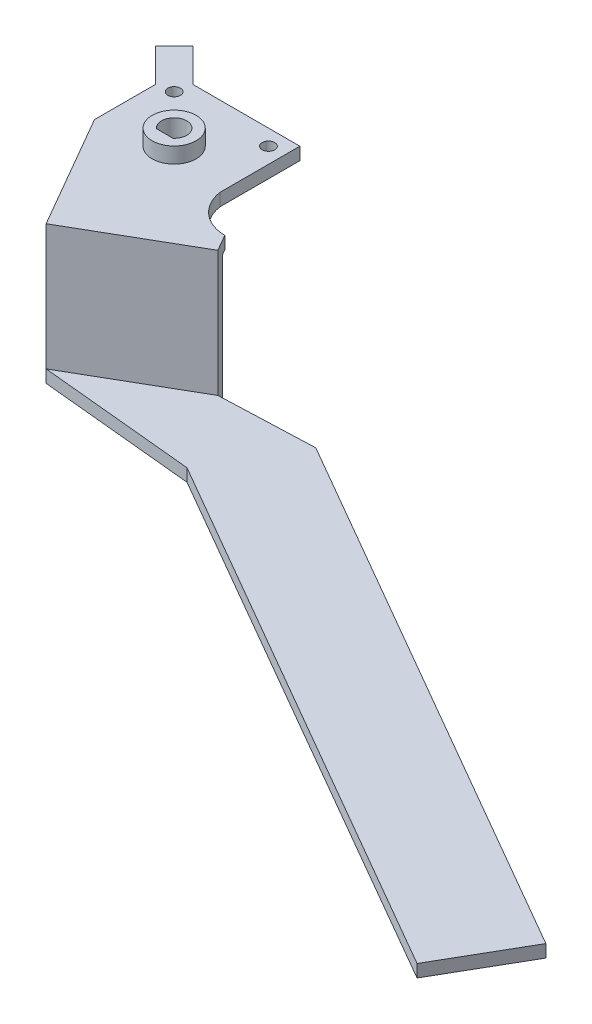
SolidWorks part; units mm, degrees
ref_plane "Front Plane" through (0, 0, 0) normal (0, 0, 1) x (1, 0, 0)
ref_plane "Top Plane" through (0, 0, 0) normal (0, 1, 0) x (1, 0, 0)
ref_plane "Right Plane" through (0, 0, 0) normal (1, 0, 0) x (0, 0, -1)
sketch "Sketch1" plane through (0, 0, 0) normal (0, 1, 0) x (1, 0, 0)
  line L0 (0, -4) -> (0, -3) construction
  line L1 (-20, 20) -> (20, 20) construction
  line L2 (-20, 20) -> (-20, -20) construction
  line L3 (-20, -20) -> (20, -20) construction
  line L4 (20, 20) -> (20, -20) construction
  line L5 (-20, 20) -> (20, -20) construction
  line L6 (-20, -20) -> (20, 20) construction
  line L11 (0, 0) -> (35.9445, -62.2576) construction
  line L12 (-20, -20) -> (20, -20) construction
  line L13 (-2.6458, -3) -> (2.6458, -3)
  line L14 (-20, -20) -> (-20, -22) construction
  line L15 (-20, -22) -> (20, -22) construction
  line L16 (20, -20) -> (20, -22) construction
  line L17 (1, -41.7321) -> (35.641, -21.7321)
  line L18 (35.641, -21.7321) -> (32.641, -16.5359)
  line L19 (1, -41.7321) -> (-20, -5.359)
  line L20 (-20, 20) -> (-20, -5.359) construction
  line L21 (20, 20) -> (20, -5.359)
  line L22 (-14, 20) -> (-24.6066, 30.6066)
  line L23 (-24.6066, 30.6066) -> (-30.6066, 24.6066)
  line L24 (-30.6066, 24.6066) -> (-20, 14)
  line L25 (-20, 14) -> (-20, -5.359)
  line L26 (-14, 20) -> (20, 20)
  circle A0 centre (0, 0) radius 4 construction
  circle A1 centre (-15, 15) radius 2
  circle A2 centre (15, 15) radius 2
  arc A3 (-2.6458, -3) -> (2.6458, -3) centre (0, 0) cw
  arc A4 (20, -5.359) -> (32.641, -16.5359) centre (32.8718, -3.5379) ccw
  point P0 (0, 0)
  point P10 (-20, 0)
  point P19 (0, -3)
  point P25 (18.3205, -31.7321)
  point P33 (32.641, -1.8453)
  point P34 (20, -5.359)
  point P35 (20, -5.359)
  dimension "D3" = 8
  dimension "D6" = 4
  dimension "D7" = 4
  dimension "D8" = 1
  dimension "D4" = 5
  dimension "D5" = 5
  dimension "D9" = 5
  dimension "D10" = 5
  dimension "D11" = 20
  dimension "D12" = 20
  dimension "D22" = 13
  dimension "D1" = 40
  dimension "D2" = 40
  dimension "D13" = 42
  dimension "D14" = 30
  dimension "D15" = 40
  dimension "D16" = 42
  dimension "D17" = 6
  dimension "D18" = 6
  dimension "D19" = 15
  dimension "D20" = 8.4853
  dimension "D21" = 6
extrude "Boss-Extrude1" add sketch "Sketch1" along normal blind 4
sketch "Sketch2" plane through (0, 4, 0) normal (0, 1, 0) x (1, 0, 0)
  line L0 (0, -4) -> (0, -3) construction
  line L1 (-2.6458, -3) -> (2.6458, -3)
  circle A0 centre (0, 0) radius 4 construction
  arc A1 (-2.6458, -3) -> (2.6458, -3) centre (0, 0) cw
  circle A2 centre (0, 0) radius 7
  point P7 (0, -3)
  dimension "D1" = 8
  dimension "D3" = 14
  dimension "D2" = 1
extrude "Boss-Extrude2" add sketch "Sketch2" along normal blind 5
sketch "Sketch7" plane through (0, 0, 0) normal (0, -1, 0) x (1, 0, 0)
  line L0 (1, 41.7321) -> (35.641, 21.7321)
  line L1 (35.641, 21.7321) -> (33.641, 18.2679)
  line L2 (35.641, 21.7321) -> (32.641, 16.5359) construction
  line L3 (33.641, 18.2679) -> (-1, 38.2679)
  line L4 (-20, 5.359) -> (1, 41.7321) construction
  line L5 (-1, 38.2679) -> (1, 41.7321)
  dimension "D1" = 40
  dimension "D2" = 4
extrude "Boss-Extrude6" add sketch "Sketch7" along normal blind 40
sketch "Sketch8" plane through (0, -40, 0) normal (0, -1, 0) x (1, 0, 0)
  line L0 (0, 0) -> (82.423, 47.587) construction
  line L2 (35.641, 21.7321) -> (32.641, 16.5359) construction
  line L3 (50.641, 46.5581) -> (65.641, 20.5774)
  line L4 (65.641, 20.5774) -> (35.641, 21.7321)
  line L5 (50.641, 46.5581) -> (1, 41.7321)
  line L6 (1, 41.7321) -> (35.641, 21.7321)
  point P9 (58.141, 33.5677)
  dimension "D1" = 30
  dimension "D2" = 30
  dimension "D3" = 30
extrude "Boss-Extrude7" add sketch "Sketch8" against normal blind 4
sketch "Sketch9" plane through (58.141, 0, 33.5677) normal (0.866, 0, 0.5) x (0.5, 0, -0.866)
  line L1 (-15, -36) -> (15, -36)
  line L2 (-15, -36) -> (-15, -40)
  line L3 (-15, -40) -> (15, -40)
  line L4 (15, -36) -> (15, -40)
extrude "Boss-Extrude8" add sketch "Sketch9" along normal blind 200
